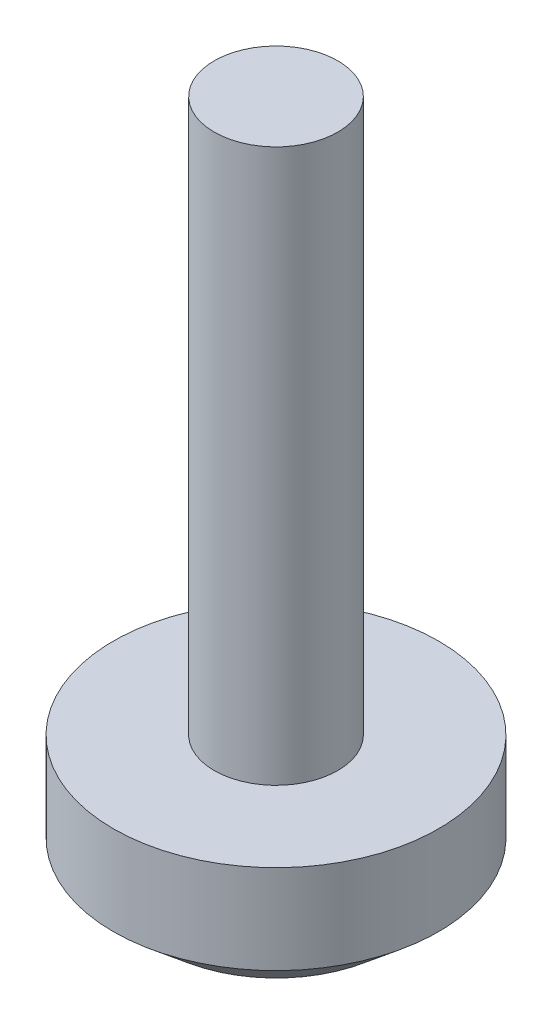
SolidWorks part; units mm, degrees
ref_plane "Front Plane" through (0, 0, 0) normal (0, 0, 1) x (1, 0, 0)
ref_plane "Top Plane" through (0, 0, 0) normal (0, 1, 0) x (1, 0, 0)
ref_plane "Right Plane" through (0, 0, 0) normal (1, 0, 0) x (0, 0, -1)
sketch "Sketch1" plane through (0, 0, 0) normal (0, 1, 0) x (1, 0, 0)
  circle A0 centre (0, 0) radius 5
  dimension "D1" = 10
extrude "Boss-Extrude1" add sketch "Sketch1" along normal blind 4
sketch "Sketch2" plane through (0, 4, 0) normal (0, 1, 0) x (1, 0, 0)
  circle A0 centre (0, 0) radius 2 construction
  circle A1 centre (0, 0) radius 1.9
  dimension "D1" = 4
  dimension "D2" = 0.1
extrude "Boss-Extrude2" add sketch "Sketch2" along normal blind 17
chamfer "Chamfer1" distance 1.5 angle 40 1 edges at (0, 0, 5)
